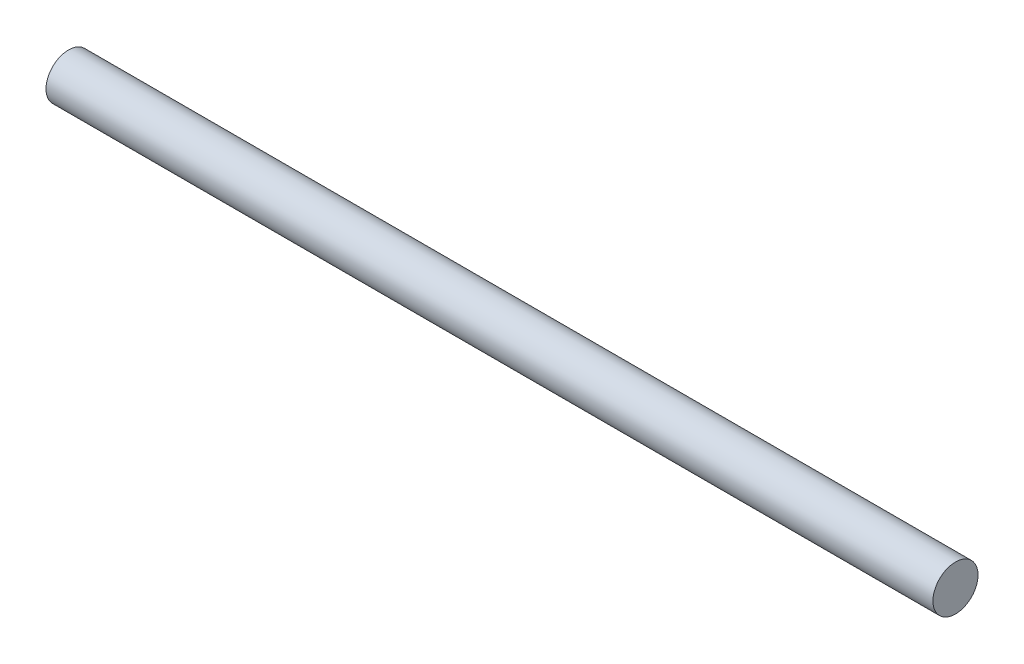
SolidWorks part; units mm, degrees
ref_plane "Alzado" through (0, 0, 0) normal (0, 0, 1) x (1, 0, 0)
ref_plane "Planta" through (0, 0, 0) normal (0, 1, 0) x (1, 0, 0)
ref_plane "Vista lateral" through (0, 0, 0) normal (1, 0, 0) x (0, 0, -1)
sketch "Croquis1" plane through (0, 0, 0) normal (1, 0, 0) x (0, 0, -1)
  circle A0 centre (0, 0) radius 4.7625
  dimension "D1" = 9.525
extrude "Saliente-Extruir1" add sketch "Croquis1" along normal blind 187.24
sketch "Croquis2" plane through (187.24, 0, 0) normal (1, 0, 0) x (0, 0, -1)
  circle A0 centre (0, 0) radius 2
  dimension "D1" = 4
sketch "Croquis3" plane through (0, 0, 0) normal (-1, 0, 0) x (0, 0, 1)
  circle A0 centre (0, 0) radius 2
